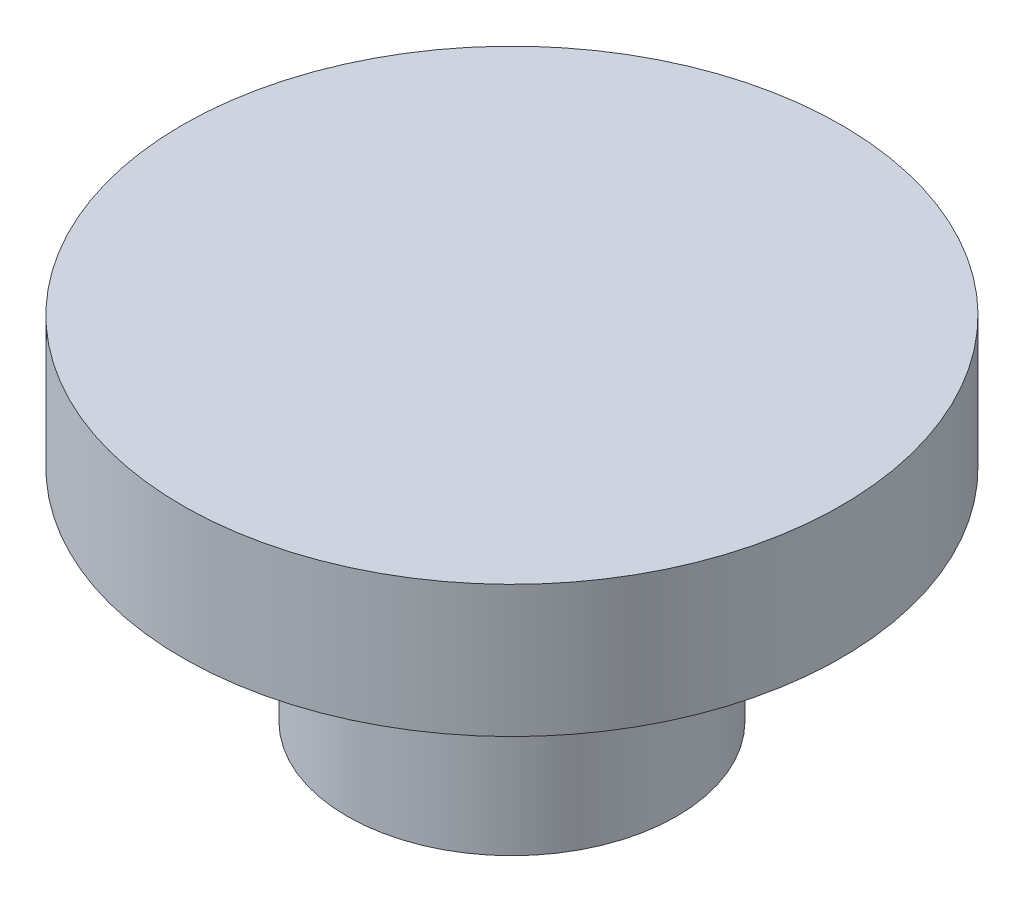
SolidWorks part; units mm, degrees
ref_plane "Front Plane" through (0, 0, 0) normal (0, 0, 1) x (1, 0, 0)
ref_plane "Top Plane" through (0, 0, 0) normal (0, 1, 0) x (1, 0, 0)
ref_plane "Right Plane" through (0, 0, 0) normal (1, 0, 0) x (0, 0, -1)
sketch "Sketch1" plane through (0, 0, 0) normal (0, 0, 1) x (1, 0, 0)
  line L0 (0, 0) -> (7.5, 0)
  line L1 (7.5, 0) -> (7.5, 8)
  line L2 (7.5, 8) -> (4.5, 8)
  line L3 (4.5, 8) -> (4.5, 10)
  line L4 (4.5, 10) -> (15, 10)
  line L5 (15, 10) -> (15, 16)
  line L6 (15, 16) -> (0, 16)
  line L7 (0, 16) -> (0, 0)
  dimension "D1" = 7.5
  dimension "D2" = 8
  dimension "D3" = 2
  dimension "D4" = 6
  dimension "D5" = 15
  dimension "D6" = 3
revolve "Revolve1" add sketch "Sketch1" angle 360 about L7
